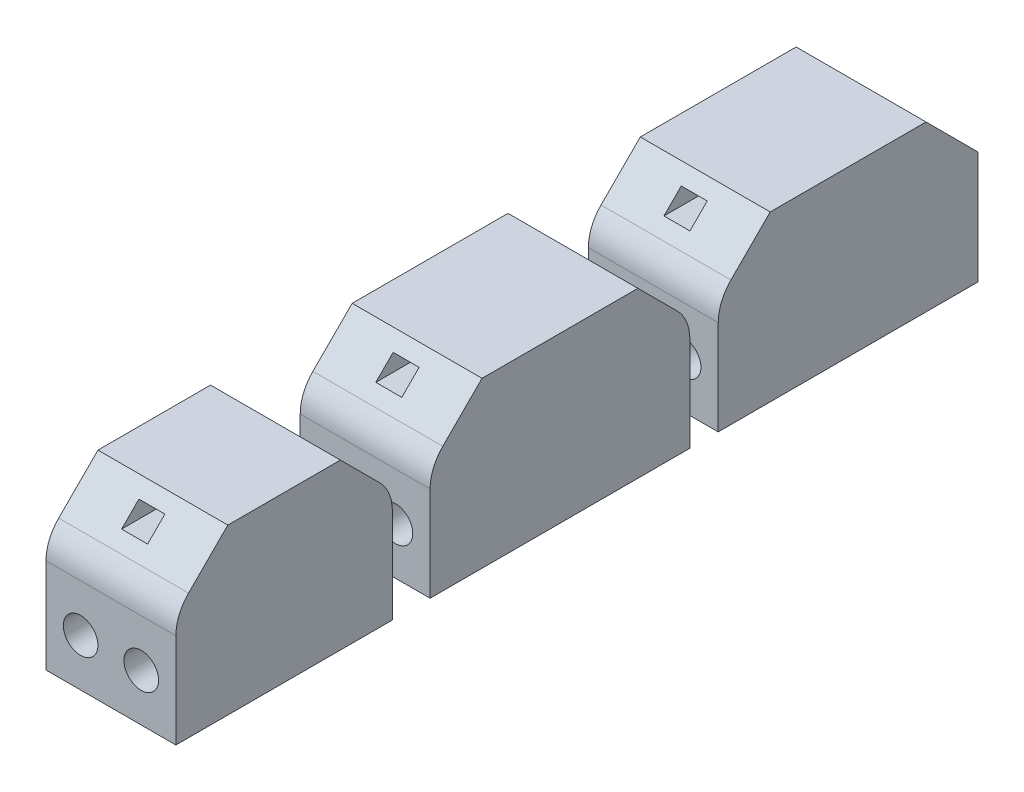
SolidWorks part; units mm, degrees
ref_plane "Front Plane" through (0, 0, 0) normal (0, 0, 1) x (1, 0, 0)
ref_plane "Top Plane" through (0, 0, 0) normal (0, 1, 0) x (1, 0, 0)
ref_plane "Right Plane" through (0, 0, 0) normal (1, 0, 0) x (0, 0, -1)
sketch "Sketch1" plane through (0, 0, 0) normal (1, 0, 0) x (0, 0, -1)
  line L0 (-31.3244, -10.2167) -> (-37.3244, -16.2167)
  line L1 (-37.3244, -16.2167) -> (-37.3244, -29.2167)
  line L2 (-37.3244, -29.2167) -> (-12.3244, -29.2167)
  line L3 (-12.3244, -29.2167) -> (-12.3244, -16.2167)
  line L4 (-12.3244, -16.2167) -> (-18.3244, -10.2167)
  line L5 (-18.3244, -10.2167) -> (-31.3244, -10.2167)
  dimension "D1" = 45
  dimension "D2" = 45
  dimension "D3" = 13
  dimension "D4" = 6
  dimension "D5" = 6
  dimension "D6" = 25
  dimension "D7" = 6
extrude "Boss-Extrude1" add sketch "Sketch1" along normal mid plane 15
sketch "Sketch2" plane through (0, 0, 0) normal (1, 0, 0) x (0, 0, -1)
  line L0 (-7.9672, -29.2167) -> (-7.9672, -16.2167)
  line L1 (-7.9672, -16.2167) -> (-1.9672, -10.2167)
  line L2 (-1.9672, -10.2167) -> (16.0328, -10.2167)
  line L3 (16.0328, -10.2167) -> (22.0328, -16.2167)
  line L4 (22.0328, -16.2167) -> (22.0328, -29.2167)
  line L5 (22.0328, -29.2167) -> (-7.9672, -29.2167)
  line L6 (-37.3244, -29.2167) -> (-12.3244, -29.2167) construction
  dimension "D1" = 45
  dimension "D2" = 45
  dimension "D4" = 30
extrude "Boss-Extrude2" add sketch "Sketch2" along normal mid plane 15 separate body
sketch "Sketch3" plane through (0, 0, 0) normal (1, 0, 0) x (0, 0, -1)
  line L0 (25.3112, -16.2167) -> (25.3112, -29.2167)
  line L1 (25.3112, -29.2167) -> (55.3112, -29.2167)
  line L2 (55.3112, -29.2167) -> (55.3112, -16.2167)
  line L3 (55.3112, -16.2167) -> (49.3112, -10.2167)
  line L4 (49.3112, -10.2167) -> (31.3112, -10.2167)
  line L5 (31.3112, -10.2167) -> (25.3112, -16.2167)
  line L6 (16.0328, -10.2167) -> (-1.9672, -10.2167) construction
  line L7 (-7.9672, -29.2167) -> (22.0328, -29.2167) construction
  line L8 (-37.3244, -29.2167) -> (-12.3244, -29.2167) construction
  dimension "D1" = 30
  dimension "D2" = 45
  dimension "D3" = 45
extrude "Boss-Extrude3" add sketch "Sketch3" along normal mid plane 15 separate body
fillet "Fillet1" radius 5 1 edges at (0, -16.2167, -25.3112)
fillet "Fillet2" radius 5 2 edges at (0, -16.2167, 7.9672) (0, -16.2167, -22.0328)
fillet "Fillet3" radius 5 2 edges at (0, -16.2167, 37.3244) (0, -16.2167, 12.3244)
sketch "Sketch4" plane through (0, 0, 0) normal (0, 0, 1) x (1, 0, 0)
  line L0 (-7.5, -18.2878) -> (-7.5, -29.2167) construction
  line L1 (7.5, -18.2878) -> (7.5, -29.2167) construction
  line L2 (-7.5, -10.2167) -> (-7.5, -14.7523) construction
  line L3 (-1.5, -11.4845) -> (1.5, -11.4845)
  line L4 (-1.5, -11.4845) -> (-1.5, -13.4845)
  line L5 (-1.5, -13.4845) -> (1.5, -13.4845)
  line L6 (1.5, -11.4845) -> (1.5, -13.4845)
  line L7 (-1.5, -11.4845) -> (1.5, -13.4845) construction
  line L8 (-1.5, -13.4845) -> (1.5, -11.4845) construction
  line L9 (7.5, -10.2167) -> (7.5, -14.7523) construction
  circle A0 centre (-3.5, -23.7523) radius 2
  circle A1 centre (3.5, -23.7523) radius 2
  point P8 (-7.5, -23.7523)
  point P11 (0, -12.4845)
  point P16 (-7.5, -12.4845)
  dimension "D1" = 4
  dimension "D2" = 4
  dimension "D3" = 4
  dimension "D4" = 4
  dimension "D5" = 3
  dimension "D6" = 2
  dimension "D7" = 6
  dimension "D8" = 6
extrude "Cut-Extrude1" cut sketch "Sketch4" against normal mid plane 200
